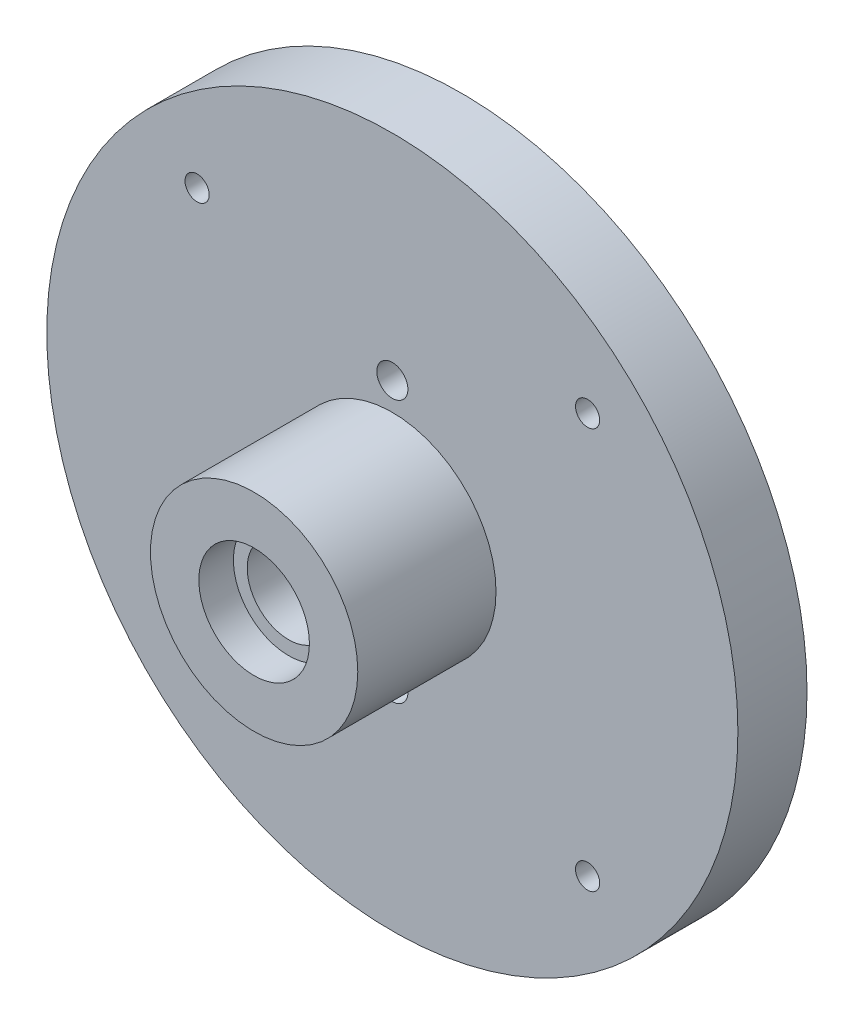
SolidWorks part; units mm, degrees
ref_plane "Front Plane" through (0, 0, 0) normal (0, 0, 1) x (1, 0, 0)
ref_plane "Top Plane" through (0, 0, 0) normal (0, 1, 0) x (1, 0, 0)
ref_plane "Right Plane" through (0, 0, 0) normal (1, 0, 0) x (0, 0, -1)
sketch "Sketch1" plane through (0, 0, 0) normal (0, 0, 1) x (1, 0, 0)
  circle A0 centre (0, 0) radius 50
  dimension "D1" = 100
extrude "Boss-Extrude1" add sketch "Sketch1" along normal blind 10
sketch "Sketch2" plane through (0, 0, 10) normal (0, 0, 1) x (1, 0, 0)
  circle A0 centre (0, 0) radius 15
  dimension "D1" = 30
extrude "Boss-Extrude2" add sketch "Sketch2" along normal blind 20
sketch "Sketch5" plane through (0, 0, 30) normal (0, 0, 1) x (1, 0, 0)
  circle A0 centre (0, 0) radius 8
  dimension "D1" = 16
extrude "Cut-Extrude2" cut sketch "Sketch5" against normal blind 5
sketch "Sketch6" plane through (0, 0, 25) normal (0, 0, 1) x (1, 0, 0)
  circle A0 centre (0, 0) radius 6
  dimension "D1" = 12
extrude "Cut-Extrude3" cut sketch "Sketch6" against normal through all
sketch "Sketch7" plane through (0, 0, 0) normal (0, 0, -1) x (-1, 0, 0)
  line L0 (0, 13.3928) -> (0, 0) construction
  line L1 (0, 0) -> (10.7142, 0) construction
  circle A0 centre (-28.25, 29) radius 1.75
  circle A1 centre (28.25, 29) radius 1.75
  circle A2 centre (28.25, -29) radius 1.75
  circle A3 centre (-28.25, -29) radius 1.75
  dimension "D1" = 3.5
  dimension "D2" = 28.25
  dimension "D3" = 29
extrude "Cut-Extrude4" cut sketch "Sketch7" against normal through all
sketch "Sketch8" plane through (0, 0, 0) normal (0, 0, -1) x (-1, 0, 0)
  line L0 (-3.4378, 0) -> (-14.1638, 0) construction
  circle A0 centre (0, 19) radius 2.25
  circle A1 centre (0, -19) radius 2.25
  dimension "D1" = 4.5
  dimension "D2" = 19
extrude "Cut-Extrude5" cut sketch "Sketch8" against normal through all
